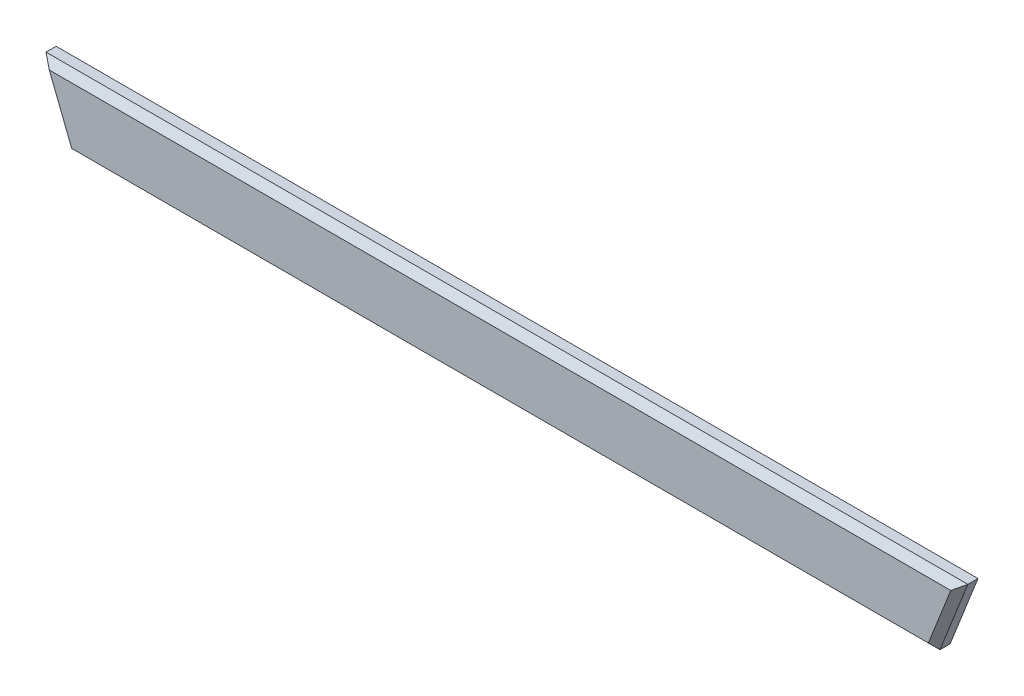
SolidWorks part; units mm, degrees
ref_plane "Front Plane" through (0, 0, 0) normal (0, 0, 1) x (1, 0, 0)
ref_plane "Top Plane" through (0, 0, 0) normal (0, 1, 0) x (1, 0, 0)
ref_plane "Right Plane" through (0, 0, 0) normal (1, 0, 0) x (0, 0, -1)
sketch "Sketch1" plane through (0, 0, 0) normal (0, 0, 1) x (1, 0, 0)
  line L0 (134.7794, -5.1508) -> (139.6443, 7.163) construction
  line L1 (100, 7.8937) -> (-100, 7.8937)
  line L2 (100, 7.8937) -> (93.9514, -7.4163)
  line L3 (93.9514, -7.4163) -> (-93.9514, -7.4163)
  line L4 (-100, 7.8937) -> (-93.9514, -7.4163)
  line L5 (100, 7.8937) -> (-93.9514, -7.4163) construction
  line L6 (93.9514, -7.4163) -> (-100, 7.8937) construction
  line L7 (-135.2985, -5.1508) -> (-140.1634, 7.163) construction
  point P0 (0, 0)
  dimension "D1" = 15.31
  dimension "D2" = 200
extrude "Boss-Extrude1" add sketch "Sketch1" along normal up to surface (3.7 mm away)
chamfer "Chamfer1" distance 1.5 angle 45 4 edges at (96.9757, 0.2387, 3.7) (0, -7.4163, 3.7) (-96.9757, 0.2387, 3.7) (0, 7.8937, 3.7)
sketch "Sketch2" plane through (0, 0, 0) normal (0, 0, -1) x (-1, 0, 0)
  circle A0 centre (-69.7404, 1.0061) radius 3
  circle A1 centre (0.2596, 1.0061) radius 3
  circle A2 centre (70.2596, 1.0061) radius 3
  dimension "D1" = 6
extrude "Boss-Extrude2" add sketch "Sketch2" along normal blind 3 draft 10
